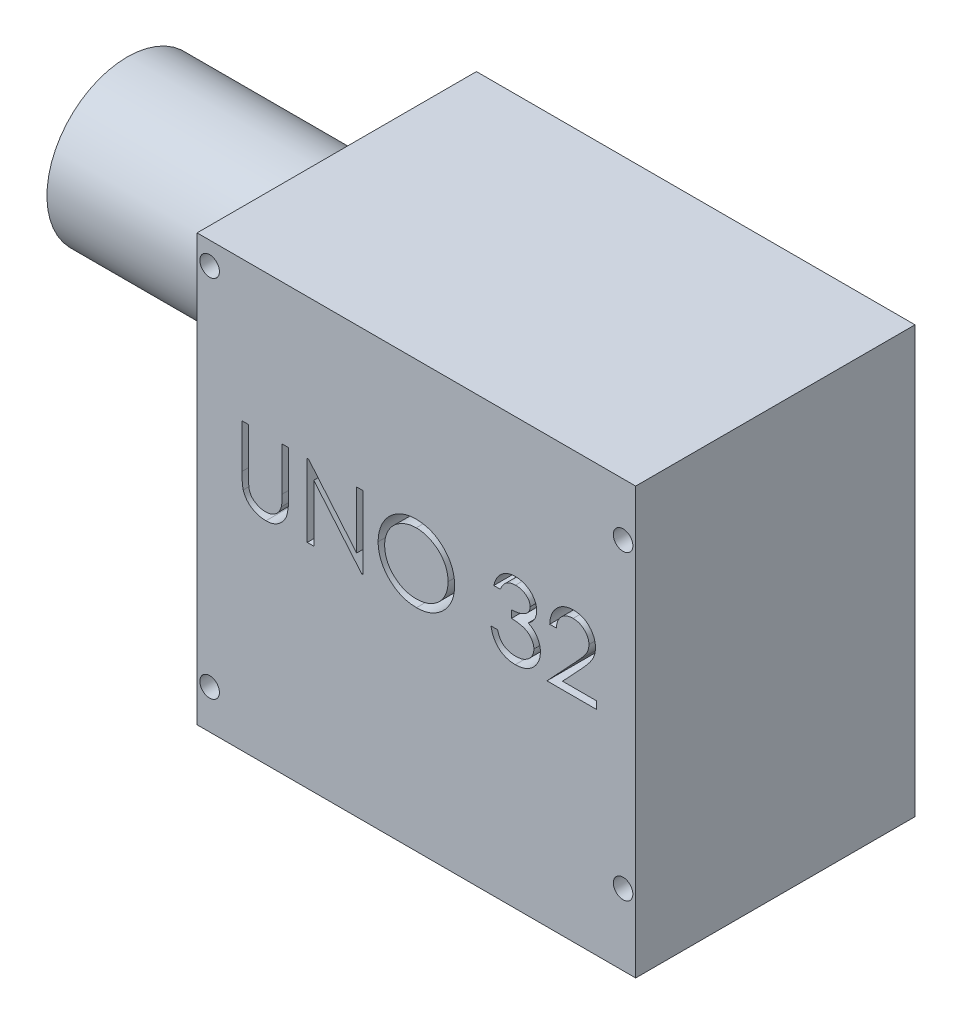
SolidWorks part; units mm, degrees
ref_plane "Front Plane" through (0, 0, 0) normal (0, 0, 1) x (1, 0, 0)
ref_plane "Top Plane" through (0, 0, 0) normal (0, 1, 0) x (1, 0, 0)
ref_plane "Right Plane" through (0, 0, 0) normal (1, 0, 0) x (0, 0, -1)
sketch "Sketch1" plane through (0, 0, 0) normal (0, 0, 1) x (1, 0, 0)
  line L1 (-86.2099, 51.9907) -> (-6.4539, 51.9907)
  line L2 (-86.2099, 51.9907) -> (-86.2099, -25.4793)
  line L3 (-86.2099, -25.4793) -> (-6.4539, -25.4793)
  line L4 (-6.4539, 51.9907) -> (-6.4539, -25.4793)
  circle A0 centre (-8.7399, 42.3387) radius 1.778
  circle A1 centre (-8.7399, -12.5253) radius 1.778
  circle A2 centre (-83.9239, 47.9267) radius 1.778
  circle A3 centre (-83.9239, -18.3673) radius 1.778
  dimension "D3" = 3.556
  dimension "D4" = 9.652
  dimension "D5" = 2.286
  dimension "D6" = 3.556
  dimension "D7" = 12.954
  dimension "D8" = 2.286
  dimension "D9" = 3.556
  dimension "D10" = 4.064
  dimension "D11" = 2.286
  dimension "D12" = 3.556
  dimension "D13" = 7.112
  dimension "D14" = 2.286
  dimension "D1" = 79.756
  dimension "D2" = 77.47
extrude "Boss-Extrude1" add sketch "Sketch1" along normal blind 50.8
sketch "Sketch2" plane through (0, 0, 50.8) normal (0, 0, 1) x (1, 0, 0)
  line L0 (-86.2099, 13.2557) -> (-6.4539, 13.2557) construction
  line L1 (-86.2099, 51.9907) -> (-86.2099, -25.4793) construction
  line L2 (-6.4539, -25.4793) -> (-6.4539, 51.9907) construction
  text T0 "UNO 32" font "Century Gothic" height in points 50
extrude "Cut-Extrude2" cut sketch "Sketch2" against normal through all
sketch "Sketch3" plane through (-86.2099, 0, 0) normal (-1, 0, 0) x (0, 0, 1)
  line L0 (50.8, 51.9907) -> (50.8, -25.4793) construction
  circle A0 centre (25.4, 33.3521) radius 14.5998
  dimension "D1" = 25.4
extrude "Boss-Extrude2" add sketch "Sketch3" along normal blind 38.1
